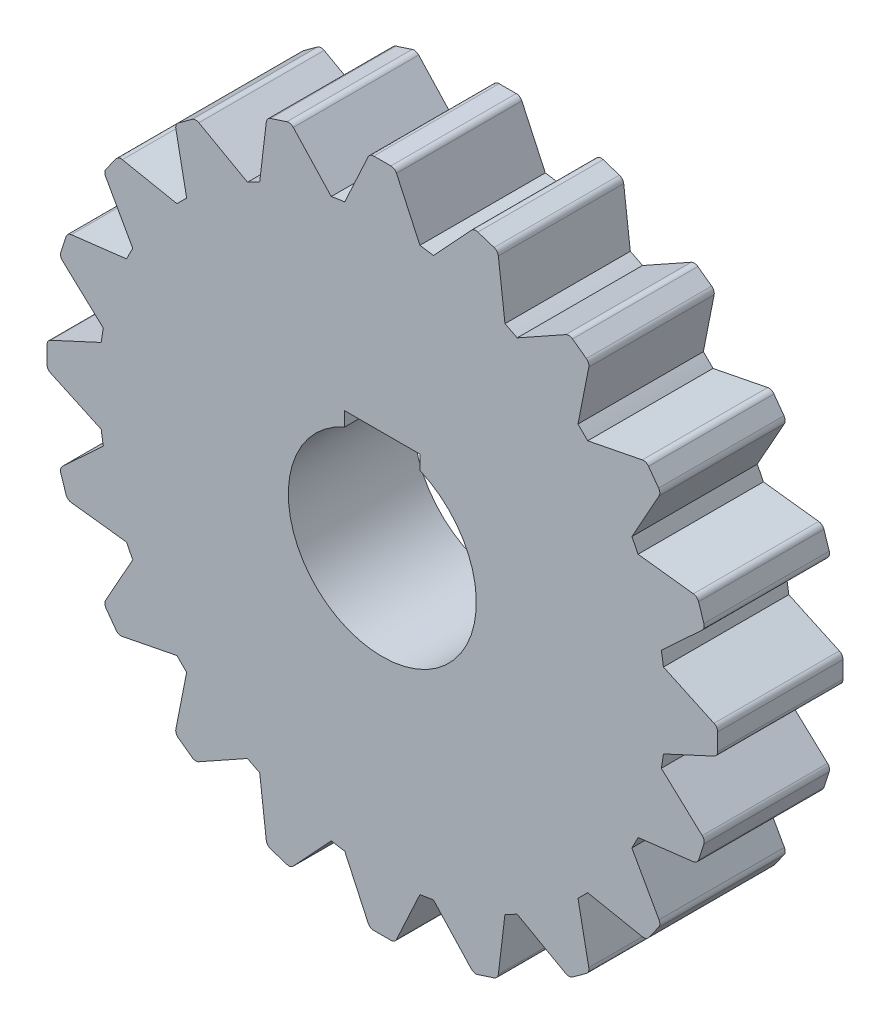
SolidWorks part; units mm, degrees
material "201 Annealed Stainless Steel (SS)"
ref_plane "Front Plane" through (0, 0, 0) normal (0, 0, 1) x (1, 0, 0)
ref_plane "Top Plane" through (0, 0, 0) normal (0, 1, 0) x (1, 0, 0)
ref_plane "Right Plane" through (0, 0, 0) normal (1, 0, 0) x (0, 0, -1)
sketch "Sketch1" plane through (0, 0, 0) normal (0, 0, 1) x (1, 0, 0)
  line L0 (0, 0) -> (0, 53.5) construction
  line L1 (0, 0) -> (15, 0) construction
  line L2 (45.25, 0) -> (53.5, 0) construction
  line L3 (0, 0) -> (45.25, 0) construction
  line L4 (0, 0) -> (66.826, 5.8465) construction
  line L5 (0, 0) -> (65.0765, 11.4747) construction
  line L6 (0, 0) -> (70.5326, 3.0795) construction
  line L7 (-1.3607, 53.5) -> (1.3607, 53.5)
  line L8 (2.2683, 52.9197) -> (6, 44.8504)
  line L9 (-2.2683, 52.9197) -> (-6, 44.8504)
  line L10 (18.5104, 49.6287) -> (19.5659, 40.8012)
  line L11 (15.2383, 51.302) -> (17.8265, 50.461)
  line L12 (14.1958, 51.0306) -> (8.1532, 44.5094)
  line L13 (32.9406, 41.4797) -> (31.2165, 32.7581)
  line L14 (30.3457, 44.0822) -> (32.5473, 42.4826)
  line L15 (29.2703, 44.1463) -> (21.5083, 39.8115)
  line L16 (44.1463, 29.2703) -> (39.8115, 21.5083)
  line L17 (42.4826, 32.5473) -> (44.0822, 30.3457)
  line L18 (41.4797, 32.9406) -> (32.7581, 31.2165)
  line L19 (51.0306, 14.1958) -> (44.5094, 8.1532)
  line L20 (50.461, 17.8265) -> (51.302, 15.2383)
  line L21 (49.6287, 18.5104) -> (40.8012, 19.5659)
  line L22 (52.9197, -2.2683) -> (44.8504, -6)
  line L23 (53.5, 1.3607) -> (53.5, -1.3607)
  line L24 (52.9197, 2.2683) -> (44.8504, 6)
  line L25 (49.6287, -18.5104) -> (40.8012, -19.5659)
  line L26 (51.302, -15.2383) -> (50.461, -17.8265)
  line L27 (51.0306, -14.1958) -> (44.5094, -8.1532)
  line L28 (41.4797, -32.9406) -> (32.7581, -31.2165)
  line L29 (44.0822, -30.3457) -> (42.4826, -32.5473)
  line L30 (44.1463, -29.2703) -> (39.8115, -21.5083)
  line L31 (6, 13.7477) -> (6, 15.9977)
  line L32 (-6, 13.7477) -> (-6, 15.9977)
  line L33 (29.2703, -44.1463) -> (21.5083, -39.8115)
  line L34 (32.5473, -42.4826) -> (30.3457, -44.0822)
  line L35 (-6, 15.9977) -> (6, 15.9977)
  line L36 (32.9406, -41.4797) -> (31.2165, -32.7581)
  line L37 (14.1958, -51.0306) -> (8.1532, -44.5094)
  line L38 (17.8265, -50.461) -> (15.2383, -51.302)
  line L39 (18.5104, -49.6287) -> (19.5659, -40.8012)
  line L40 (-2.2683, -52.9197) -> (-6, -44.8504)
  line L41 (1.3607, -53.5) -> (-1.3607, -53.5)
  line L42 (2.2683, -52.9197) -> (6, -44.8504)
  line L43 (-18.5104, -49.6287) -> (-19.5659, -40.8012)
  line L44 (-15.2383, -51.302) -> (-17.8265, -50.461)
  line L45 (-14.1958, -51.0306) -> (-8.1532, -44.5094)
  line L46 (-32.9406, -41.4797) -> (-31.2165, -32.7581)
  line L47 (-30.3457, -44.0822) -> (-32.5473, -42.4826)
  line L48 (-29.2703, -44.1463) -> (-21.5083, -39.8115)
  line L49 (-44.1463, -29.2703) -> (-39.8115, -21.5083)
  line L50 (-42.4826, -32.5473) -> (-44.0822, -30.3457)
  line L51 (-41.4797, -32.9406) -> (-32.7581, -31.2165)
  line L52 (-51.0306, -14.1958) -> (-44.5094, -8.1532)
  line L53 (-50.461, -17.8265) -> (-51.302, -15.2383)
  line L54 (-49.6287, -18.5104) -> (-40.8012, -19.5659)
  line L55 (-52.9197, 2.2683) -> (-44.8504, 6)
  line L56 (-53.5, -1.3607) -> (-53.5, 1.3607)
  line L57 (-52.9197, -2.2683) -> (-44.8504, -6)
  line L58 (-49.6287, 18.5104) -> (-40.8012, 19.5659)
  line L59 (-51.302, 15.2383) -> (-50.461, 17.8265)
  line L60 (-51.0306, 14.1958) -> (-44.5094, 8.1532)
  line L61 (-41.4797, 32.9406) -> (-32.7581, 31.2165)
  line L62 (-44.0822, 30.3457) -> (-42.4826, 32.5473)
  line L63 (-44.1463, 29.2703) -> (-39.8115, 21.5083)
  line L64 (-29.2703, 44.1463) -> (-21.5083, 39.8115)
  line L65 (-32.5473, 42.4826) -> (-30.3457, 44.0822)
  line L66 (-32.9406, 41.4797) -> (-31.2165, 32.7581)
  line L67 (-14.1958, 51.0306) -> (-8.1532, 44.5094)
  line L68 (-17.8265, 50.461) -> (-15.2383, 51.302)
  line L69 (-18.5104, 49.6287) -> (-19.5659, 40.8012)
  arc A0 (-6, 44.8504) -> (-8.1532, 44.5094) centre (0, 0) ccw
  circle A1 centre (0, 0) radius 53.5 construction
  arc A2 (2.2683, 52.9197) -> (1.3607, 53.5) centre (1.3607, 52.5) ccw
  arc A3 (-2.2683, 52.9197) -> (-1.3607, 53.5) centre (-1.3607, 52.5) cw
  arc A4 (18.5104, 49.6287) -> (17.8265, 50.461) centre (17.5175, 49.51) ccw
  arc A5 (14.1958, 51.0306) -> (15.2383, 51.302) centre (14.9293, 50.3509) cw
  arc A6 (32.9406, 41.4797) -> (32.5473, 42.4826) centre (31.9596, 41.6736) ccw
  arc A7 (29.2703, 44.1463) -> (30.3457, 44.0822) centre (29.7579, 43.2732) cw
  arc A8 (44.1463, 29.2703) -> (44.0822, 30.3457) centre (43.2732, 29.7579) ccw
  arc A9 (41.4797, 32.9406) -> (42.4826, 32.5473) centre (41.6736, 31.9596) cw
  arc A10 (51.0306, 14.1958) -> (51.302, 15.2383) centre (50.3509, 14.9293) ccw
  arc A11 (49.6287, 18.5104) -> (50.461, 17.8265) centre (49.51, 17.5175) cw
  arc A12 (52.9197, -2.2683) -> (53.5, -1.3607) centre (52.5, -1.3607) ccw
  arc A13 (52.9197, 2.2683) -> (53.5, 1.3607) centre (52.5, 1.3607) cw
  arc A14 (49.6287, -18.5104) -> (50.461, -17.8265) centre (49.51, -17.5175) ccw
  arc A15 (51.0306, -14.1958) -> (51.302, -15.2383) centre (50.3509, -14.9293) cw
  arc A16 (41.4797, -32.9406) -> (42.4826, -32.5473) centre (41.6736, -31.9596) ccw
  arc A17 (44.1463, -29.2703) -> (44.0822, -30.3457) centre (43.2732, -29.7579) cw
  arc A18 (29.2703, -44.1463) -> (30.3457, -44.0822) centre (29.7579, -43.2732) ccw
  arc A19 (32.9406, -41.4797) -> (32.5473, -42.4826) centre (31.9596, -41.6736) cw
  arc A20 (14.1958, -51.0306) -> (15.2383, -51.302) centre (14.9293, -50.3509) ccw
  arc A21 (18.5104, -49.6287) -> (17.8265, -50.461) centre (17.5175, -49.51) cw
  arc A22 (-2.2683, -52.9197) -> (-1.3607, -53.5) centre (-1.3607, -52.5) ccw
  arc A23 (2.2683, -52.9197) -> (1.3607, -53.5) centre (1.3607, -52.5) cw
  arc A24 (-18.5104, -49.6287) -> (-17.8265, -50.461) centre (-17.5175, -49.51) ccw
  arc A25 (-14.1958, -51.0306) -> (-15.2383, -51.302) centre (-14.9293, -50.3509) cw
  arc A26 (-32.9406, -41.4797) -> (-32.5473, -42.4826) centre (-31.9596, -41.6736) ccw
  arc A27 (-29.2703, -44.1463) -> (-30.3457, -44.0822) centre (-29.7579, -43.2732) cw
  arc A28 (-44.1463, -29.2703) -> (-44.0822, -30.3457) centre (-43.2732, -29.7579) ccw
  arc A29 (-41.4797, -32.9406) -> (-42.4826, -32.5473) centre (-41.6736, -31.9596) cw
  arc A30 (-51.0306, -14.1958) -> (-51.302, -15.2383) centre (-50.3509, -14.9293) ccw
  arc A31 (-49.6287, -18.5104) -> (-50.461, -17.8265) centre (-49.51, -17.5175) cw
  arc A32 (-52.9197, 2.2683) -> (-53.5, 1.3607) centre (-52.5, 1.3607) ccw
  arc A33 (-52.9197, -2.2683) -> (-53.5, -1.3607) centre (-52.5, -1.3607) cw
  arc A34 (-49.6287, 18.5104) -> (-50.461, 17.8265) centre (-49.51, 17.5175) ccw
  arc A35 (-51.0306, 14.1958) -> (-51.302, 15.2383) centre (-50.3509, 14.9293) cw
  arc A36 (-41.4797, 32.9406) -> (-42.4826, 32.5473) centre (-41.6736, 31.9596) ccw
  arc A37 (-44.1463, 29.2703) -> (-44.0822, 30.3457) centre (-43.2732, 29.7579) cw
  arc A38 (-29.2703, 44.1463) -> (-30.3457, 44.0822) centre (-29.7579, 43.2732) ccw
  arc A39 (-32.9406, 41.4797) -> (-32.5473, 42.4826) centre (-31.9596, 41.6736) cw
  arc A40 (-14.1958, 51.0306) -> (-15.2383, 51.302) centre (-14.9293, 50.3509) ccw
  arc A41 (-18.5104, 49.6287) -> (-17.8265, 50.461) centre (-17.5175, 49.51) cw
  arc A42 (8.1532, 44.5094) -> (6, 44.8504) centre (0, 0) ccw
  arc A43 (21.5083, 39.8115) -> (19.5659, 40.8012) centre (0, 0) ccw
  arc A44 (32.7581, 31.2165) -> (31.2165, 32.7581) centre (0, 0) ccw
  arc A45 (40.8012, 19.5659) -> (39.8115, 21.5083) centre (0, 0) ccw
  arc A46 (-6, 13.7477) -> (6, 13.7477) centre (0, 0) ccw
  arc A47 (44.5094, -8.1532) -> (44.8504, -6) centre (0, 0) ccw
  arc A48 (44.8504, 6) -> (44.5094, 8.1532) centre (0, 0) ccw
  arc A49 (39.8115, -21.5083) -> (40.8012, -19.5659) centre (0, 0) ccw
  arc A50 (31.2165, -32.7581) -> (32.7581, -31.2165) centre (0, 0) ccw
  arc A51 (19.5659, -40.8012) -> (21.5083, -39.8115) centre (0, 0) ccw
  arc A52 (6, -44.8504) -> (8.1532, -44.5094) centre (0, 0) ccw
  arc A53 (-8.1532, -44.5094) -> (-6, -44.8504) centre (0, 0) ccw
  arc A54 (-21.5083, -39.8115) -> (-19.5659, -40.8012) centre (0, 0) ccw
  arc A55 (-32.7581, -31.2165) -> (-31.2165, -32.7581) centre (0, 0) ccw
  arc A56 (-40.8012, -19.5659) -> (-39.8115, -21.5083) centre (0, 0) ccw
  arc A57 (-44.8504, -6) -> (-44.5094, -8.1532) centre (0, 0) ccw
  arc A58 (-44.5094, 8.1532) -> (-44.8504, 6) centre (0, 0) ccw
  arc A59 (-39.8115, 21.5083) -> (-40.8012, 19.5659) centre (0, 0) ccw
  arc A60 (-31.2165, 32.7581) -> (-32.7581, 31.2165) centre (0, 0) ccw
  arc A61 (-19.5659, 40.8012) -> (-21.5083, 39.8115) centre (0, 0) ccw
  point P1 (6, 14.8727)
  point P4 (49.6387, 5.8465)
  point P16 (2, 53.5)
  point P177 (0, 0)
  point P188 (0, 0)
  dimension "D1" = 15
  dimension "D2" = 12
  dimension "D3" = 2.25
  dimension "D5" = 6
  dimension "D7" = 8.25
  dimension "D11" = 2
  dimension "D6" = 15
  dimension "D13" = 1
  dimension "D4" = 15.9977
  dimension "D10" = 2.5
  dimension "D8" = 5
  dimension "D9" = 10
  dimension "D12" = 6
  dimension "D14" = 20
extrude "Boss-Extrude1" add sketch "Sketch1" against normal blind 20
